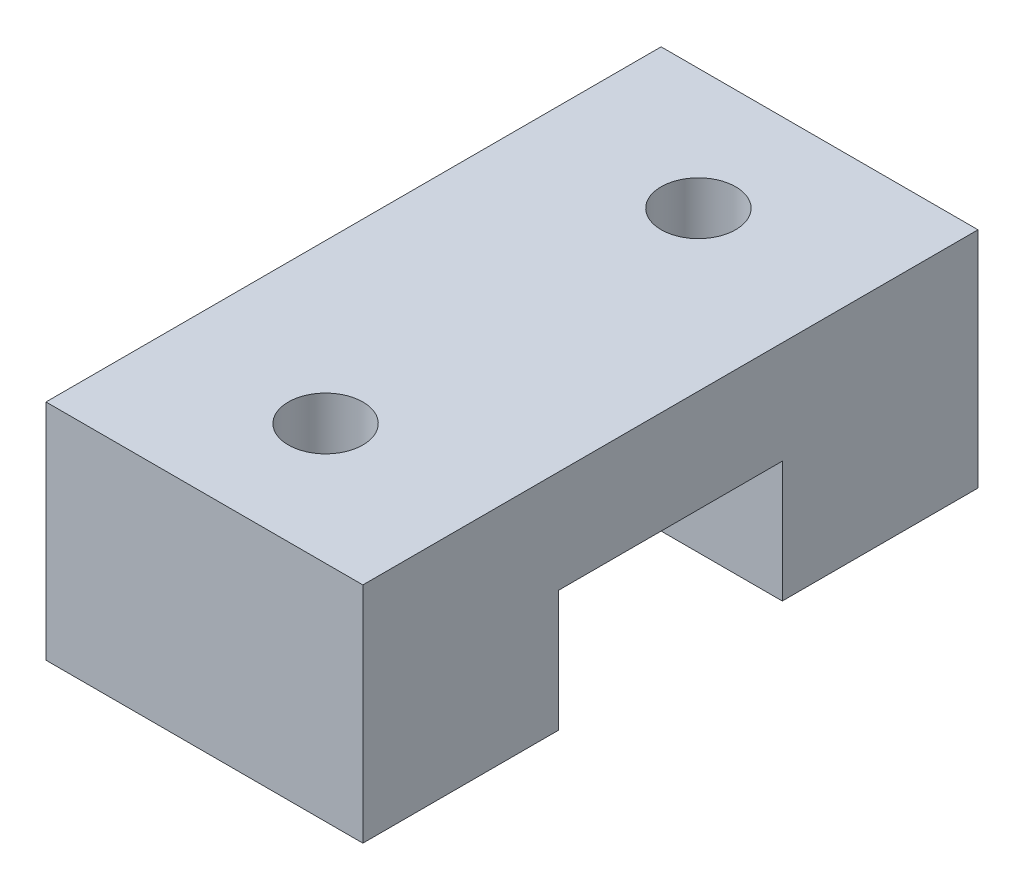
SolidWorks part; units mm, degrees
ref_plane "Alzado" through (0, 0, 0) normal (0, 0, 1) x (1, 0, 0)
ref_plane "Planta" through (0, 0, 0) normal (0, 1, 0) x (1, 0, 0)
ref_plane "Vista lateral" through (0, 0, 0) normal (1, 0, 0) x (0, 0, -1)
sketch "Croquis1" plane through (0, 0, 0) normal (0, 1, 0) x (1, 0, 0)
  line L14 (-8.5, -16.5) -> (8.5, -16.5)
  line L15 (-8.5, -16.5) -> (-8.5, 16.5)
  line L16 (-8.5, 16.5) -> (8.5, 16.5)
  line L17 (8.5, -16.5) -> (8.5, 16.5)
  line L18 (-8.5, -16.5) -> (8.5, 16.5) construction
  line L19 (-8.5, 16.5) -> (8.5, -16.5) construction
  point P0 (0, 0)
  dimension "D1" = 17
  dimension "D2" = 33
extrude "Saliente-Extruir1" add sketch "Croquis1" along normal blind 12
sketch "Croquis2" plane through (0, 12, 0) normal (0, 1, 0) x (1, 0, 0)
  line L0 (0, 0) -> (3.1956, 0) construction
  circle A0 centre (0, 10) radius 2
  circle A1 centre (0, -10) radius 2
  point P7 (0, 0)
  point P10 (0, 0)
  dimension "D1" = 4
  dimension "D2" = 20
extrude "Cortar-Extruir1" cut sketch "Croquis2" against normal through all
sketch "Croquis3" plane through (8.5, 0, 0) normal (1, 0, 0) x (0, 0, -1)
  line L1 (-6, 0) -> (6, 0)
  line L2 (-6, 0) -> (-6, 6.5)
  line L3 (-6, 6.5) -> (6, 6.5)
  line L4 (6, 0) -> (6, 6.5)
  point P4 (0, 0)
  dimension "D1" = 6.5
  dimension "D2" = 12
extrude "Cortar-Extruir2" cut sketch "Croquis3" against normal through all
